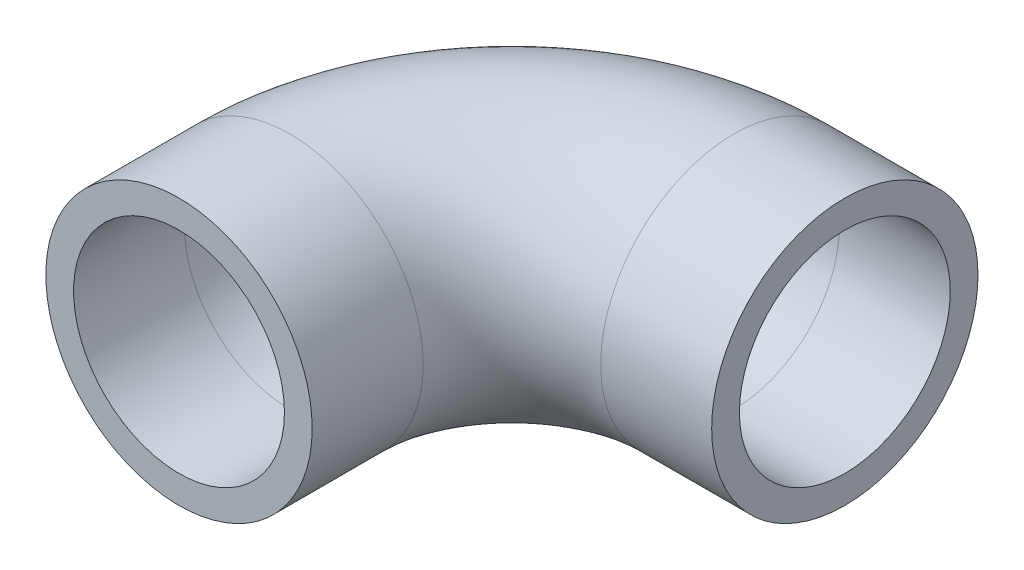
SolidWorks part; units mm, degrees
material "PVC Rigid"
ref_plane "Front Plane" through (0, 0, 0) normal (0, 0, 1) x (1, 0, 0)
ref_plane "Top Plane" through (0, 0, 0) normal (0, 1, 0) x (1, 0, 0)
ref_plane "Right Plane" through (0, 0, 0) normal (1, 0, 0) x (0, 0, -1)
sketch "Sketch1" plane through (0, 0, 0) normal (0, 1, 0) x (1, 0, 0)
  line L0 (0, 0) -> (0, 25.4)
  line L1 (50.8, 76.2) -> (76.2, 76.2)
  arc A0 (0, 25.4) -> (50.8, 76.2) centre (50.8, 25.4) cw
  point P6 (0, 76.2)
  dimension "D4" = 50.8
  dimension "D1" = 90
  dimension "D2" = 76.2
  dimension "D3" = 76.2
sketch "Sketch2" plane through (0, 0, 0) normal (0, 0, 1) x (1, 0, 0)
  circle A0 centre (0, 0) radius 24.13
  circle A1 centre (0, 0) radius 30.48
  dimension "D1" = 48.26
  dimension "D2" = 6.35
sweep "Sweep1" add profiles "Sketch2" path "Sketch1"
